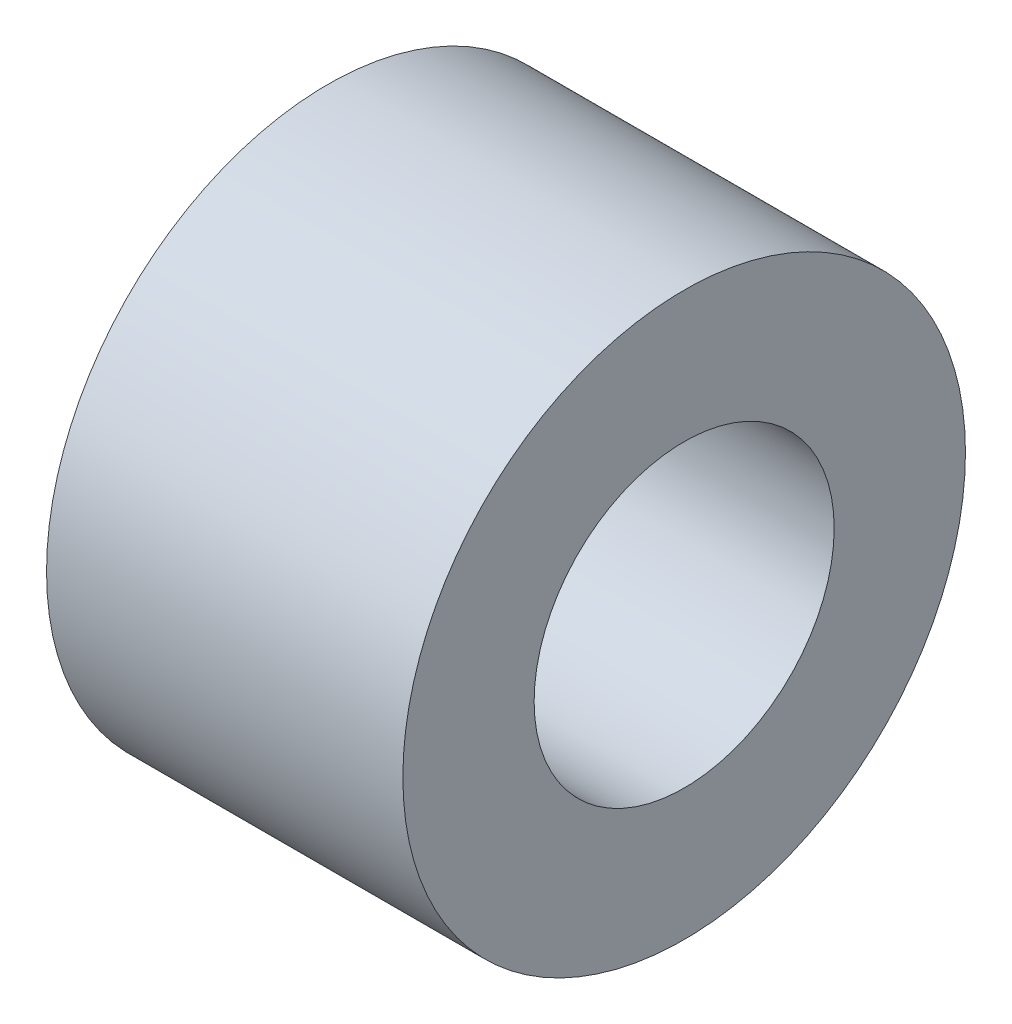
SolidWorks part; units mm, degrees
material "6061-T6 (SS)"
ref_plane "Front Plane" through (0, 0, 0) normal (0, 0, 1) x (1, 0, 0)
ref_plane "Top Plane" through (0, 0, 0) normal (0, 1, 0) x (1, 0, 0)
ref_plane "Right Plane" through (0, 0, 0) normal (1, 0, 0) x (0, 0, -1)
sketch "Sketch1" plane through (0, 0, 0) normal (1, 0, 0) x (0, 0, -1)
  circle A0 centre (0, 0) radius 1.6
  circle A1 centre (0, 0) radius 3
  dimension "D1" = 3.2
  dimension "D2" = 6
extrude "Boss-Extrude1" add sketch "Sketch1" along normal blind 3.8
